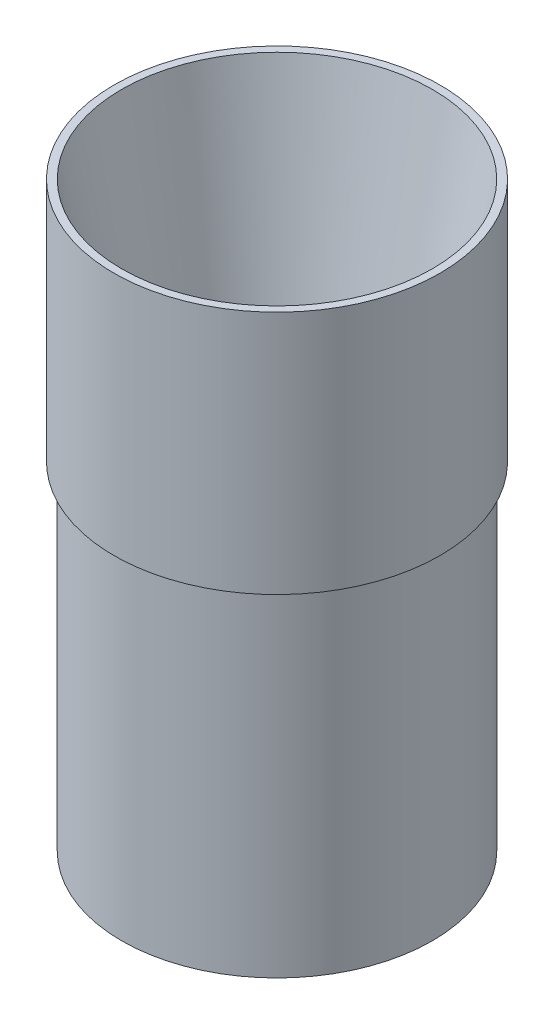
SolidWorks part; units mm, degrees
material "6061-T6 (SS)"
ref_plane "Front Plane" through (0, 0, 0) normal (0, 0, 1) x (1, 0, 0)
ref_plane "Top Plane" through (0, 0, 0) normal (0, 1, 0) x (1, 0, 0)
ref_plane "Right Plane" through (0, 0, 0) normal (1, 0, 0) x (0, 0, -1)
sketch "Sketch1" plane through (0, 0, 0) normal (0, 0, 1) x (1, 0, 0)
  line L13 (2.3813, 0) -> (0, 0)
  line L14 (0, 181.3458) -> (23.0187, 50.8)
  line L15 (23.0187, 50.8) -> (2.3812, 50.8)
  line L16 (2.3812, 50.8) -> (2.3813, 0)
  line L18 (0, 181.3458) -> (-2.3813, 181.3458)
  line L19 (-2.3813, 181.3458) -> (-2.3812, 105.1458)
  line L20 (-2.3812, 105.1458) -> (0, 105.1458)
  line L21 (0, 105.1458) -> (0, 0)
  line L22 (48.4187, 283.9393) -> (48.4188, -39.5083) construction
  dimension "D1" = 80
  dimension "D2" = 2.3813
  dimension "D3" = 2.3813
  dimension "D4" = 2.3813
  dimension "D5" = 50.8
  dimension "D6" = 25.4
  dimension "D7" = 76.2
  dimension "D8" = 50.8
revolve "Revolve1" add sketch "Sketch1" angle 360 about L22
